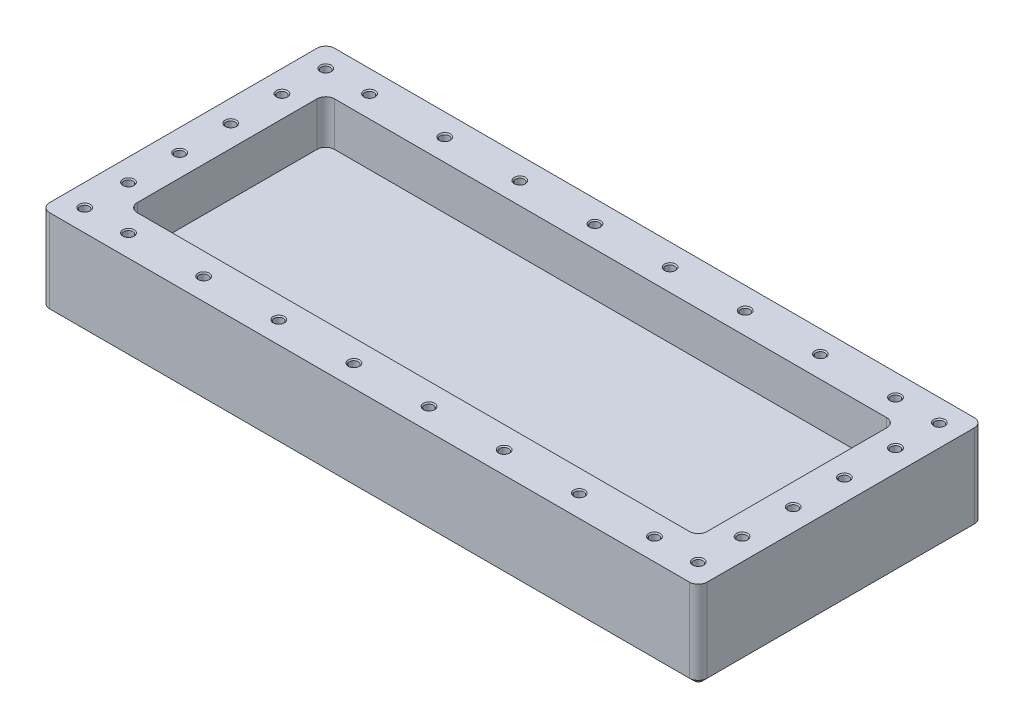
SolidWorks part; units mm, degrees
material "AISI Type 316L stainless steel"
ref_plane "Front Plane" through (0, 0, 0) normal (0, 0, 1) x (1, 0, 0)
ref_plane "Top Plane" through (0, 0, 0) normal (0, 1, 0) x (1, 0, 0)
ref_plane "Right Plane" through (0, 0, 0) normal (1, 0, 0) x (0, 0, -1)
sketch "Sketch1" plane through (0, 0, 0) normal (0, 1, 0) x (1, 0, 0)
  line L1 (75, -32.5) -> (-75, -32.5)
  line L2 (75, -32.5) -> (75, 32.5)
  line L3 (75, 32.5) -> (-75, 32.5)
  line L4 (-75, -32.5) -> (-75, 32.5)
  line L5 (75, -32.5) -> (-75, 32.5) construction
  line L6 (75, 32.5) -> (-75, -32.5) construction
  point P0 (0, 0)
  dimension "D1" = 65
  dimension "D2" = 150
extrude "Boss-Extrude1" add sketch "Sketch1" along normal blind 20
hole_wizard "1/8 NPT Tapped Hole1" positions "Sketch2" profile "Sketch3" size "1/8" standard "ANSI Inch" end condition through all
sketch "Sketch2" plane through (0, 0, 0) normal (0, -1, 0) x (-1, 0, 0)
  line L1 (-75, -32.5) -> (-75, 32.5) construction
  point P0 (-60, 0)
  dimension "D1" = 15
sketch "Sketch3" plane through (60, 0, 0) normal (1, 0, 0) x (0, 0, -1)
  line L0 (0, 0) -> (0, 20)
  line L1 (0, 20) -> (4.2164, 20)
  line L2 (-4.5374, 6.92) -> (-4.7446, 0) construction
  line L3 (4.2164, 20) -> (4.2164, 6.92)
  line L4 (4.2164, 6.92) -> (4.5374, 6.92)
  line L5 (4.5374, 6.92) -> (4.7446, 0)
  line L7 (4.7446, 0) -> (0, 0)
  line L8 (0, -6.35) -> (0, 107.95) construction
  line L11 (-4.2164, 6.92) -> (-4.5374, 6.92) construction
  dimension "Thru Tap Drill Dia." = 8.4328
  dimension "Thru Tap Drill Depth" = 20
  dimension "Thread Dia." = 9.4892
  dimension "Thread Angle" = 3.43
  dimension "Thread Depth" = 6.92
cosmetic thread "Hole Thread1" parameters "D1"=6.92, "D2"=10.2867
sketch "Sketch4" plane through (0, 20, 0) normal (0, 1, 0) x (1, 0, 0)
  line L8 (-65, 22.5) -> (-65, -22.5)
  line L9 (-65, -22.5) -> (65, -22.5)
  line L10 (65, -22.5) -> (65, 22.5)
  line L11 (65, 22.5) -> (-65, 22.5)
  line L12 (-65, 22.5) -> (-65, -22.5)
  line L13 (-65, -22.5) -> (65, -22.5)
  line L14 (65, -22.5) -> (65, 22.5)
  line L15 (65, 22.5) -> (-65, 22.5)
  dimension "D1" = 10
extrude "Cut-Extrude1" cut sketch "Sketch4" against normal blind 10
sketch "Sketch9" plane through (0, 20, 0) normal (0, 1, 0) x (1, 0, 0)
  line L0 (-75, 32.5) -> (-65, 22.5) construction
  line L1 (70, -27.5) -> (-70, -27.5) construction
  line L2 (70, -27.5) -> (70, 27.5) construction
  line L3 (70, 27.5) -> (-70, 27.5) construction
  line L4 (-70, -27.5) -> (-70, 27.5) construction
  line L5 (70, -27.5) -> (-70, 27.5) construction
  line L6 (70, 27.5) -> (-70, -27.5) construction
  line L7 (-75, 0) -> (75, 0) construction
  line L8 (-75, 32.5) -> (-75, -32.5) construction
  line L9 (75, -32.5) -> (75, 32.5) construction
  line L10 (0, -11) -> (0, 11) construction
  point P0 (0, 0)
  point P10 (-42.8571, 27.5)
  point P11 (-60, 27.5)
  point P12 (-25.7143, 27.5)
  point P14 (-8.5714, 27.5)
  point P15 (8.5714, 27.5)
  point P16 (25.7143, 27.5)
  point P17 (42.8571, 27.5)
  point P18 (60, 27.5)
  point P19 (-70, 17.5)
  point P20 (-70, 5.8333)
  point P21 (-70, -5.8333)
  point P22 (-70, -17.5)
  point P29 (60, -27.5)
  point P30 (42.8571, -27.5)
  point P31 (25.7143, -27.5)
  point P32 (8.5714, -27.5)
  point P33 (-8.5714, -27.5)
  point P34 (-25.7143, -27.5)
  point P35 (-42.8571, -27.5)
  point P36 (-60, -27.5)
  point P40 (70, -17.5)
  point P41 (70, -5.8333)
  point P42 (70, 5.8333)
  point P43 (70, 17.5)
  dimension "D2" = 10
  dimension "D3" = 10
  dimension "D5" = 10
  dimension "D6" = 10
  dimension "D1" = 8
  dimension "D4" = 4
hole_wizard "M2.5 Tapped Hole1" positions "3DSketch4" profile "Sketch10" tap size "M2.5" standard "GB"
sketch3d "3DSketch4"
  point P0 (-70, 20, -17.5)
  point P3 (-70, 20, -5.8333)
  point P6 (-70, 20, 5.8333)
  point P9 (-70, 20, 17.5)
  point P12 (-60, 20, 27.5)
  point P15 (-42.8571, 20, 27.5)
  point P18 (-25.7143, 20, 27.5)
  point P21 (-8.5714, 20, 27.5)
  point P24 (8.5714, 20, 27.5)
  point P27 (25.7143, 20, 27.5)
  point P30 (42.8571, 20, 27.5)
  point P33 (60, 20, 27.5)
  point P36 (-60, 20, -27.5)
  point P39 (-42.8571, 20, -27.5)
  point P42 (-25.7143, 20, -27.5)
  point P45 (-8.5714, 20, -27.5)
  point P48 (8.5714, 20, -27.5)
  point P51 (25.7143, 20, -27.5)
  point P54 (42.8571, 20, -27.5)
  point P57 (60, 20, -27.5)
  point P60 (70, 20, -17.5)
  point P63 (70, 20, -5.8333)
  point P66 (70, 20, 5.8333)
  point P69 (70, 20, 17.5)
  point P72 (70, 20, -27.5)
  point P75 (70, 20, 27.5)
  point P78 (-70, 20, -27.5)
  point P81 (-70, 20, 27.5)
sketch "Sketch10" plane through (-70, 20, -17.5) normal (1, 0, 0) x (0, 0, 1)
  line L0 (0, 0) -> (0, 8.6159)
  line L1 (0, 8.6159) -> (1.025, 8)
  line L2 (1.025, 8) -> (1.025, 0.25)
  line L3 (1.025, 0.25) -> (1.275, 0)
  line L5 (1.275, 0) -> (0, 0)
  line L6 (-1.025, 0.25) -> (-1.275, 0) construction
  line L10 (0, 8.6159) -> (-1.025, 8) construction
  line L11 (0, -6.35) -> (0, 107.95) construction
  dimension "Tap Drill Dia." = 2.05
  dimension "Tap Drill Depth" = 8
  dimension "Near C'Sink Dia." = 2.55
  dimension "Near C'Sink Angle" = 90
  dimension "Drill Angle" = 118
fillet "Fillet1" radius 2 4 edges at (75, 10, -32.5) (75, 10, 32.5) (-75, 10, 32.5) (-75, 10, -32.5)
fillet "Fillet2" radius 2 4 edges at (65, 15, 22.5) (-65, 15, 22.5) (-65, 15, -22.5) (65, 15, -22.5)
sketch "Sketch5" plane through (0, 0, 0) normal (0, -1, 0) x (-1, 0, 0)
  line L0 (0, 0) -> (75, 0) construction
  line L1 (75, 30.5) -> (75, -30.5) construction
  line L2 (-12.75, 7) -> (42.75, -7) construction
  point P0 (42.75, -7)
  point P1 (-12.75, -7)
  point P2 (42.75, 7)
  point P3 (-12.75, 7)
  point P7 (15, 0)
  dimension "D1" = 55.5
  dimension "D2" = 14
  dimension "D3" = 15
hole_wizard "M2.5 Tapped Hole2" positions "3DSketch2" profile "Sketch8" tap size "M2.5" standard "GB"
sketch3d "3DSketch2"
  point P0 (-42.75, 0, 7)
  point P3 (12.75, 0, 7)
  point P6 (-42.75, 0, -7)
  point P9 (12.75, 0, -7)
sketch "Sketch8" plane through (-42.75, 0, 7) normal (1, 0, 0) x (0, 0, -1)
  line L0 (0, 0) -> (0, 8.6159)
  line L1 (0, 8.6159) -> (1.025, 8)
  line L2 (1.025, 8) -> (1.025, 0.25)
  line L3 (1.025, 0.25) -> (1.275, 0)
  line L5 (1.275, 0) -> (0, 0)
  line L6 (-1.025, 0.25) -> (-1.275, 0) construction
  line L10 (0, 8.6159) -> (-1.025, 8) construction
  line L11 (0, -6.35) -> (0, 107.95) construction
  dimension "Tap Drill Dia." = 2.05
  dimension "Tap Drill Depth" = 8
  dimension "Near C'Sink Dia." = 2.55
  dimension "Near C'Sink Angle" = 90
  dimension "Drill Angle" = 118
chamfer "Chamfer1" distance 1 angle 45 8 edges at (0, 0, -32.5) (-74.4142, 0, -31.9142) (74.4142, 0, -31.9142) (-75, 0, 0) (75, 0, 0) (-74.4142, 0, 31.9142) (74.4142, 0, 31.9142) (0, 0, 32.5)
